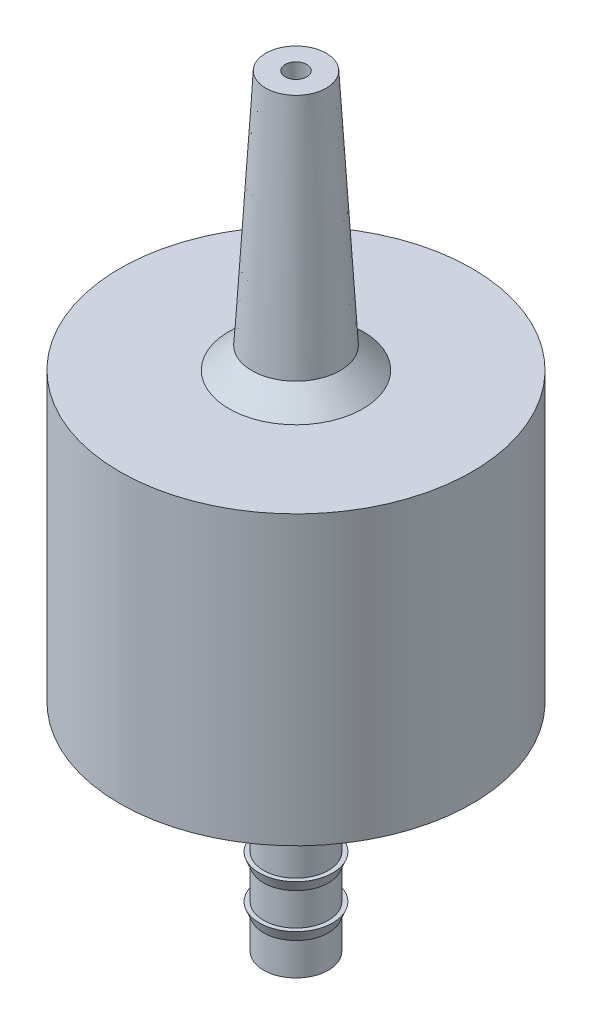
SolidWorks part; units mm, degrees
ref_plane "Plano frontal" through (0, 0, 0) normal (0, 0, 1) x (1, 0, 0)
ref_plane "Plano superior" through (0, 0, 0) normal (0, 1, 0) x (1, 0, 0)
ref_plane "Plano direito" through (0, 0, 0) normal (1, 0, 0) x (0, 0, -1)
sketch "Esboço1" plane through (0, 0, 0) normal (0, 0, 1) x (1, 0, 0)
  line L0 (0, 23.0581) -> (0, 0) construction
  line L1 (2.1, 0) -> (8.15, 0)
  line L2 (1.5, -13.3) -> (8.15, -13.3)
  line L3 (8.15, 0) -> (8.15, -13.3)
  line L4 (1, -23.3) -> (1.5, -23.3)
  line L5 (1.5, -23.3) -> (1.5, -21.8)
  line L6 (1.5, -21.8) -> (1.7, -21.3)
  line L7 (1.5, -21.3) -> (1.7, -21.3)
  line L8 (1.5, -19.3) -> (1.7, -19.3)
  line L9 (1.7, -19.3) -> (1.5, -19.8)
  line L10 (1.5, -17.3) -> (1.7, -17.3)
  line L11 (1.7, -17.3) -> (1.5, -17.8)
  line L12 (1.5, -15.3) -> (1.7, -15.3)
  line L13 (1.7, -15.3) -> (1.5, -15.8)
  line L14 (1.5, -15.3) -> (1.5, -13.3)
  line L15 (1.5, -17.3) -> (1.5, -15.8)
  line L16 (1.5, -19.3) -> (1.5, -17.8)
  line L17 (1.5, -21.3) -> (1.5, -19.8)
  line L19 (1, -23.3) -> (1.25, 0)
  line L20 (0, -23.3) -> (0, -18.0198) construction
  line L21 (0, 0) -> (1.25, 0) construction
  line L22 (0, 0) -> (0, -23.3) construction
  line L23 (0, 12) -> (0.5, 12) construction
  line L24 (0.5, 12) -> (1.25, 0)
  line L25 (0.5, 12) -> (1.4, 12)
  line L26 (1.4, 12) -> (2.1, 0)
  dimension "D1" = 8.15
  dimension "D2" = 13.3
  dimension "D3" = 1.5
  dimension "D4" = 10
  dimension "D5" = 1.5
  dimension "D6" = 0.2
  dimension "D7" = 0.5
  dimension "D8" = 1.5
  dimension "D9" = 1.5
  dimension "D10" = 1.5
  dimension "D11" = 1
  dimension "D12" = 1.25
  dimension "D13" = 0.5
  dimension "D14" = 12
  dimension "D15" = 1.4
  dimension "D16" = 2.1
revolve "Revolução1" add sketch "Esboço1" angle 360 about L0
sketch "Esboço2" plane through (0, 0, 0) normal (0, 0, 1) x (1, 0, 0)
  line L0 (1.5, -14.8) -> (2.5, -13.3)
  line L1 (-8.15, -13.3) -> (8.15, -13.3) construction
  line L2 (1.5, -15.3) -> (1.5, -13.3) construction
  line L3 (1.5, -14.8) -> (1.5, -13.3)
  line L4 (1.5, -13.3) -> (2.5, -13.3)
  line L5 (0, 0.658) -> (0, -16.2351) construction
  line L6 (2.1, 0) -> (2.0418, 0.9983)
  line L7 (2.0418, 0.9983) -> (3.1, 0)
  line L8 (2.1, 0) -> (3.1, 0)
  line L9 (8.15, 0) -> (-8.15, 0) construction
  line L10 (2.1, 0) -> (1.4, 12) construction
  dimension "D1" = 1.5
  dimension "D2" = 1
  dimension "D3" = 1
  dimension "D4" = 1
revolve "Revolução2" add sketch "Esboço2" angle 360 about L5
